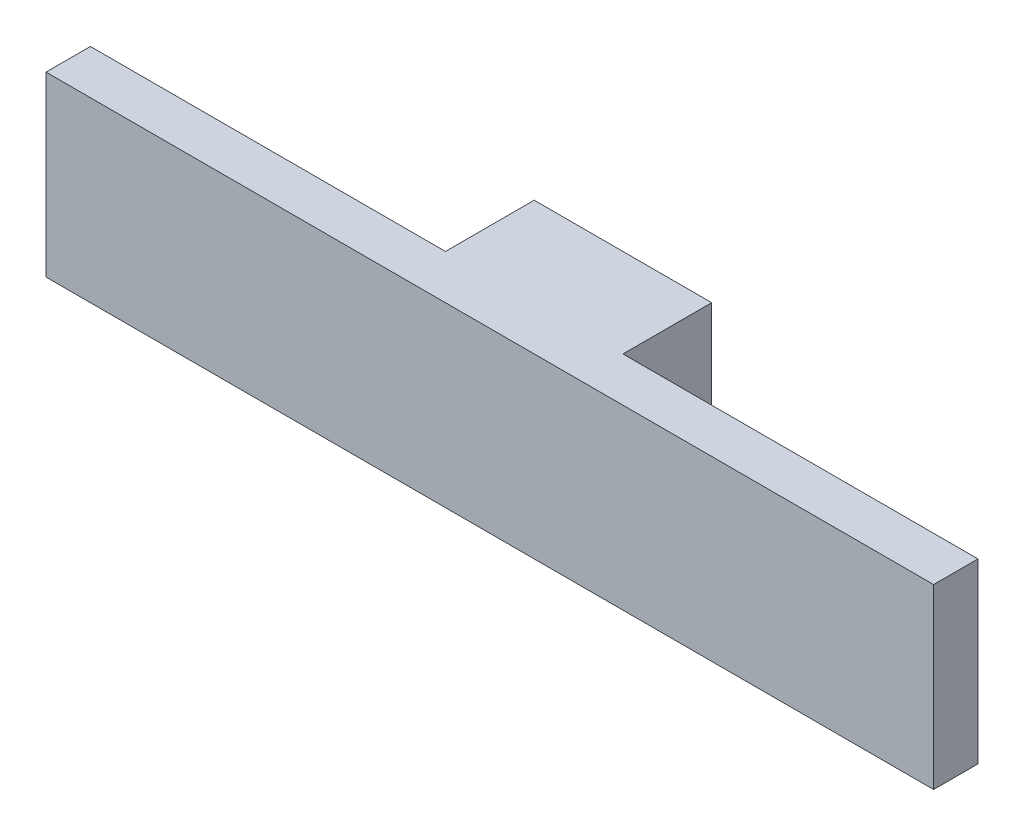
SolidWorks part; units mm, degrees
ref_plane "Přední rovina" through (0, 0, 0) normal (0, 0, 1) x (1, 0, 0)
ref_plane "Horní rovina" through (0, 0, 0) normal (0, 1, 0) x (1, 0, 0)
ref_plane "Pravá rovina" through (0, 0, 0) normal (1, 0, 0) x (0, 0, -1)
sketch "Sketch2" plane through (0, 0, 0) normal (0, 1, 0) x (1, 0, 0)
  line L0 (0, -15) -> (0, 0) construction
  line L1 (50, -15) -> (-50, -15)
  line L2 (50, -15) -> (50, -10)
  line L3 (50, -10) -> (10, -10)
  line L7 (-10, 0) -> (10, 0)
  line L8 (10, -10) -> (10, 0)
  line L9 (-10, -10) -> (-10, 0)
  line L10 (-50, -10) -> (-10, -10)
  line L11 (-50, -15) -> (-50, -10)
  dimension "D1" = 50
  dimension "D2" = 5
  dimension "D3" = 10
  dimension "D4" = 10
extrude "Boss-Extrude1" add sketch "Sketch2" along normal blind 20
